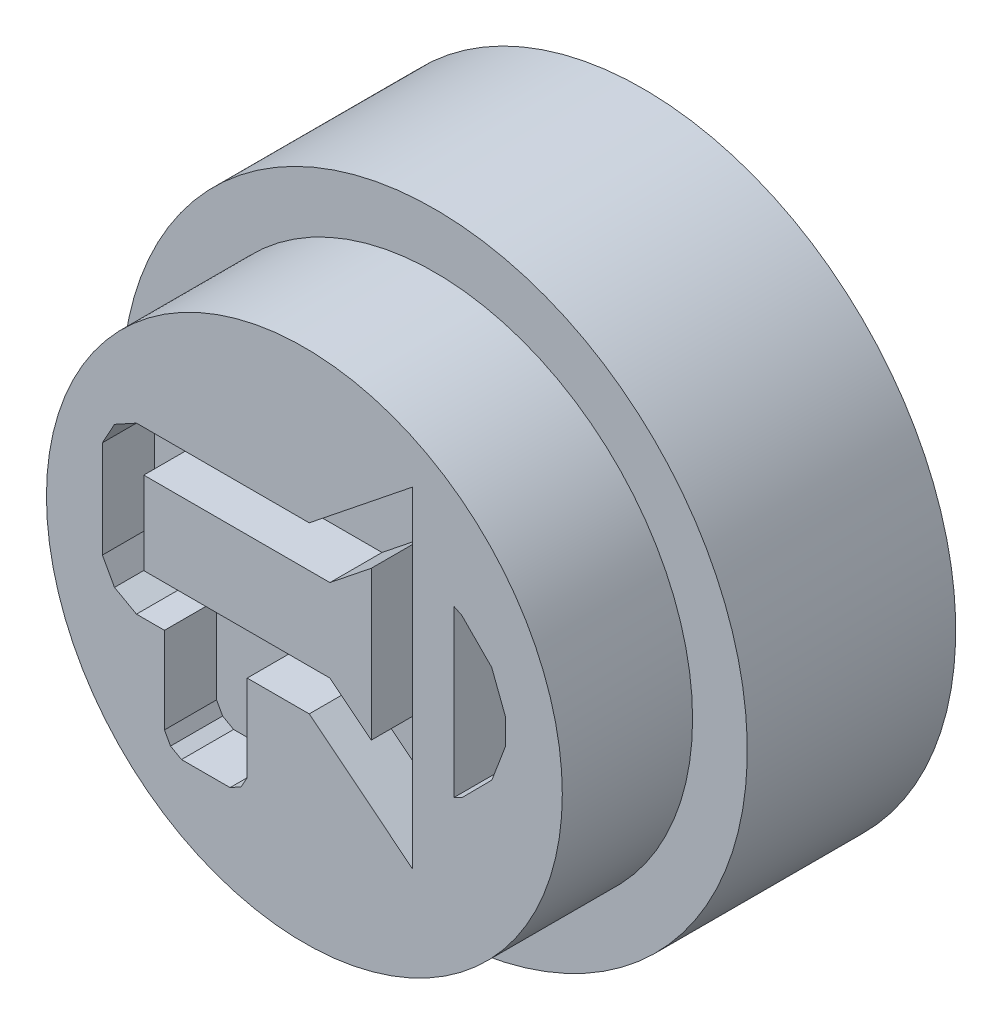
SolidWorks part; units mm, degrees
ref_plane "Plan de face" through (0, 0, 0) normal (0, 0, 1) x (1, 0, 0)
ref_plane "Plan de dessus" through (0, 0, 0) normal (0, 1, 0) x (1, 0, 0)
ref_plane "Plan de droite" through (0, 0, 0) normal (1, 0, 0) x (0, 0, -1)
sketch "Esquisse1" plane through (0, 0, 0) normal (0, 0, 1) x (1, 0, 0)
  circle A0 centre (0, 0) radius 9.9
  dimension "D1" = 19.8
extrude "Boss.-Extru.1" add sketch "Esquisse1" along normal blind 15
sketch "Esquisse4" plane through (0, 0, 15) normal (0, 0, 1) x (1, 0, 0)
  circle A0 centre (0, 0) radius 9.9 construction
  line B0 (0.1865, 4.1598) -> (-6.1635, 4.1598)
  line B1 (-6.1635, 4.1598) -> (-6.4446, 4.1598)
  line B2 (-6.4446, 4.1598) -> (-7.288, 3.6968)
  line B3 (-7.288, 3.6968) -> (-7.751, 2.8534)
  line B4 (-7.751, 2.8534) -> (-7.751, 2.5723)
  line B5 (-7.751, 2.5723) -> (-7.751, -0.6027)
  line B6 (-7.751, -0.6027) -> (-7.751, -0.8796)
  line B7 (-7.751, -0.8796) -> (-7.288, -1.723)
  line B8 (-7.288, -1.723) -> (-6.4446, -2.1902)
  line B9 (-6.4446, -2.1902) -> (-6.1635, -2.1902)
  line B10 (-6.1635, -2.1902) -> (-5.3697, -2.1902)
  line B11 (-5.3697, -2.1902) -> (-5.3697, -5.3652)
  line B12 (-5.3697, -5.3652) -> (-5.3697, -5.5016)
  line B13 (-5.3697, -5.5016) -> (-5.1382, -5.9233)
  line B14 (-5.1382, -5.9233) -> (-4.7165, -6.1589)
  line B15 (-4.7165, -6.1589) -> (-4.576, -6.1589)
  line B16 (-4.576, -6.1589) -> (-2.9885, -6.1589)
  line B17 (-2.9885, -6.1589) -> (-2.852, -6.1589)
  line B18 (-2.852, -6.1589) -> (-2.4304, -5.9233)
  line B19 (-2.4304, -5.9233) -> (-2.1947, -5.5016)
  line B20 (-2.1947, -5.5016) -> (-2.1947, -5.3652)
  line B21 (-2.1947, -5.3652) -> (-2.1947, -2.1902)
  line B22 (-2.1947, -2.1902) -> (0.1865, -2.1902)
  line B23 (0.1865, -2.1902) -> (4.1553, -5.3652)
  line B24 (4.1553, -5.3652) -> (4.1553, 7.3348)
  line B25 (4.1553, 7.3348) -> (0.1865, 4.1598)
  line B26 (2.5678, -1.8719) -> (0.9803, -0.6027)
  line B27 (0.9803, -0.6027) -> (-6.1635, -0.6027)
  line B28 (-6.1635, -0.6027) -> (-6.1635, 2.5723)
  line B29 (-6.1635, 2.5723) -> (0.9803, 2.5723)
  line B30 (0.9803, 2.5723) -> (2.5678, 3.8415)
  line B31 (2.5678, 3.8415) -> (2.5678, -1.8719)
  line B32 (7.7271, 0.9848) -> (7.7271, 0.5176)
  line B33 (7.7271, 0.5176) -> (7.1939, -0.8879)
  line B34 (7.1939, -0.8879) -> (6.0487, -2.0413)
  line B35 (6.0487, -2.0413) -> (5.7428, -2.1902)
  line B36 (5.7428, -2.1902) -> (5.7428, 4.1598)
  line B37 (5.7428, 4.1598) -> (6.0446, 4.011)
  line B38 (6.0446, 4.011) -> (7.1898, 2.8575)
  line B39 (7.1898, 2.8575) -> (7.7271, 1.4561)
  line B40 (7.7271, 1.4561) -> (7.7271, 0.9848)
sketch_block_instance "bullhorn-outline-1"
sketch_block "Bloc1"
extrude "Enlèv. mat.-Extru.1" cut sketch "Esquisse4" against normal blind 2
sketch "Esquisse6" plane through (0, 0, 0) normal (0, 0, -1) x (-1, 0, 0)
  circle A0 centre (0, 0) radius 9.9
extrude "Enlèv. mat.-Extru.2" cut sketch "Esquisse6" against normal blind 10
sketch "Esquisse8" plane through (0, 0, 10) normal (0, 0, -1) x (-1, 0, 0)
  circle A0 centre (0, 0) radius 12
  dimension "D1" = 24
extrude "Boss.-Extru.2" add sketch "Esquisse8" along normal blind 8
